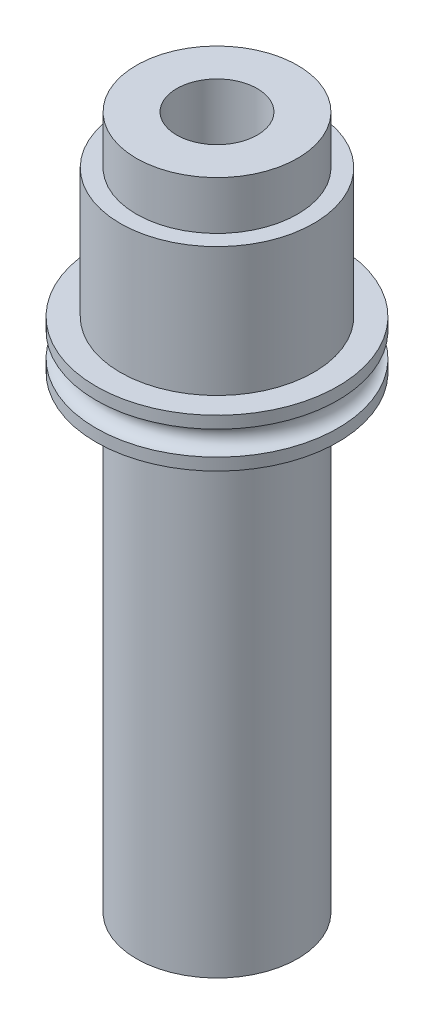
SolidWorks part; units mm, degrees
ref_plane "Alzado" through (0, 0, 0) normal (0, 0, 1) x (1, 0, 0)
ref_plane "Planta" through (0, 0, 0) normal (0, 1, 0) x (1, 0, 0)
ref_plane "Vista lateral" through (0, 0, 0) normal (1, 0, 0) x (0, 0, -1)
sketch "Croquis1" plane through (0, 0, 0) normal (0, 1, 0) x (1, 0, 0)
  circle A0 centre (0, 0) radius 7.5
  dimension "D1" = 15
extrude "Saliente-Extruir1" add sketch "Croquis1" along normal blind 3
ref_axis "Eje1" through (0, 3, 0) along (0, -1, 0)
sketch "Croquis2" plane through (0, 0, 0) normal (1, 0, 0) x (0, 0, -1)
  line L0 (7.5, 0) -> (7.5, 3) construction
  circle A0 centre (7.5, 1.5) radius 0.75
  dimension "D1" = 1.5
revolve "Cortar-Revolución1" cut sketch "Croquis2" angle 360 about axis through (0, 3, 0) along (0, -1, 0)
sketch "Croquis4" plane through (0, 0, 0) normal (0, -1, 0) x (1, 0, 0)
  circle A0 centre (0, 0) radius 5
  dimension "D1" = 10
extrude "Saliente-Extruir2" add sketch "Croquis4" along normal blind 29
sketch "Croquis5" plane through (0, 3, 0) normal (0, 1, 0) x (1, 0, 0)
  circle A0 centre (0, 0) radius 6
  dimension "D1" = 12
extrude "Saliente-Extruir3" add sketch "Croquis5" along normal blind 8
sketch "Croquis6" plane through (0, 11, 0) normal (0, 1, 0) x (1, 0, 0)
  circle A0 centre (0, 0) radius 5
  dimension "D1" = 10
extrude "Saliente-Extruir4" add sketch "Croquis6" along normal blind 3
sketch "Croquis3" plane through (0, -29, 0) normal (0, 1, 0) x (1, 0, 0)
  circle A0 centre (0, 0) radius 2.5
  dimension "D1" = 5
extrude "Cortar-Extruir1" cut sketch "Croquis3" along normal through all
